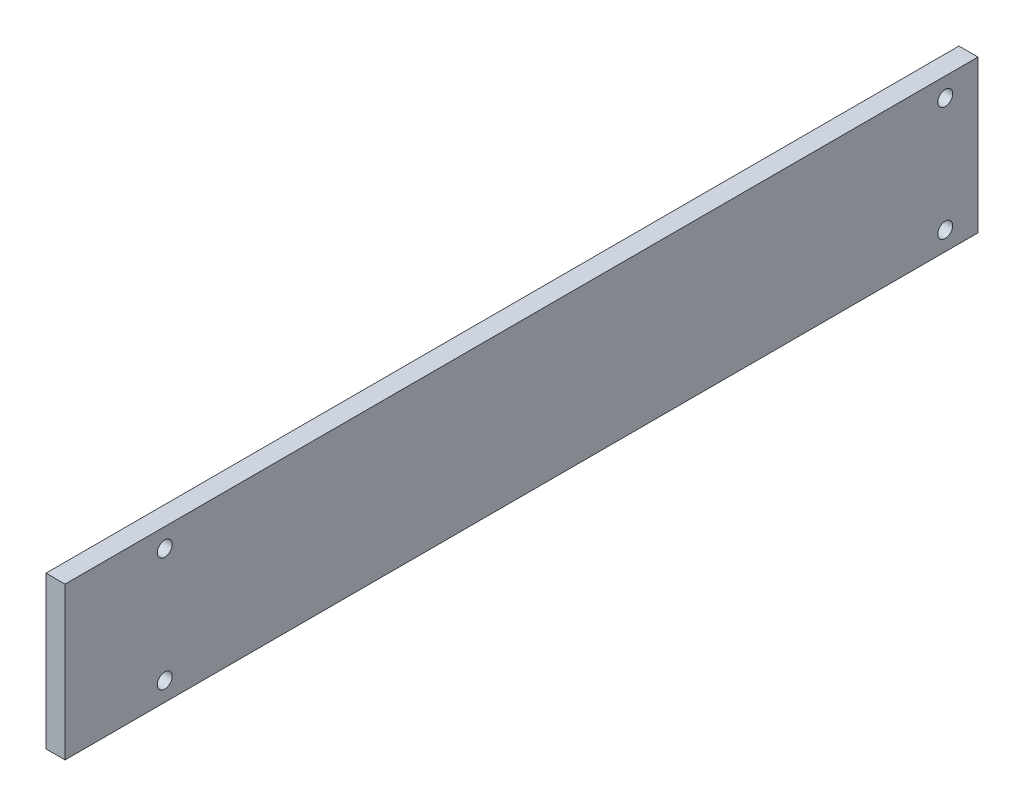
SolidWorks part; units mm, degrees
material "6061-T6 (SS)"
ref_plane "Front Plane" through (0, 0, 0) normal (0, 0, 1) x (1, 0, 0)
ref_plane "Top Plane" through (0, 0, 0) normal (0, 1, 0) x (1, 0, 0)
ref_plane "Right Plane" through (0, 0, 0) normal (1, 0, 0) x (0, 0, -1)
sketch "Sketch1" plane through (0, 0, 0) normal (1, 0, 0) x (0, 0, -1)
  line L1 (-152.273, 25.4) -> (152.273, 25.4)
  line L2 (-152.273, 25.4) -> (-152.273, -25.4)
  line L3 (-152.273, -25.4) -> (152.273, -25.4)
  line L4 (152.273, 25.4) -> (152.273, -25.4)
  line L5 (-152.273, 25.4) -> (152.273, -25.4) construction
  line L6 (-152.273, -25.4) -> (152.273, 25.4) construction
  point P0 (0, 0)
  dimension "D1" = 50.8
  dimension "D2" = 304.546
extrude "Boss-Extrude1" add sketch "Sketch1" along normal blind 6.35
sketch "Sketch2" plane through (6.35, 0, 0) normal (1, 0, 0) x (0, 0, -1)
  line L0 (152.273, -25.4) -> (152.273, 25.4) construction
  line L1 (-118.999, 19.05) -> (141.351, 19.05) construction
  line L2 (-118.999, 19.05) -> (-118.999, -19.05) construction
  line L3 (-118.999, -19.05) -> (141.351, -19.05) construction
  line L4 (141.351, 19.05) -> (141.351, -19.05) construction
  line L5 (-118.999, 19.05) -> (141.351, -19.05) construction
  line L6 (-118.999, -19.05) -> (141.351, 19.05) construction
  line L7 (-152.273, 25.4) -> (-152.273, -25.4) construction
  point P0 (11.176, 0)
  point P7 (0, 0)
  dimension "D1" = 10.922
  dimension "D2" = 33.274
  dimension "D3" = 38.1
hole_wizard "#10 Clearance Hole1" positions "Sketch3" profile "Sketch4" hole size "#10" standard "ANSI Inch" end condition through all
sketch "Sketch3" plane through (6.35, 0, 0) normal (1, 0, 0) x (0, 0, -1)
  point P0 (-118.999, 19.05)
  point P3 (-118.999, -19.05)
  point P6 (141.351, -19.05)
  point P9 (141.351, 19.05)
sketch "Sketch4" plane through (6.35, 19.05, 118.999) normal (0, 1, 0) x (0, 0, -1)
  line L0 (0, 0) -> (0, 6.35)
  line L1 (0, 6.35) -> (2.4892, 6.35)
  line L2 (2.4892, 6.35) -> (2.4892, 0)
  line L5 (2.4892, 0) -> (0, 0)
  line L11 (0, -6.35) -> (0, 107.95) construction
  dimension "Thru Hole Dia." = 4.9784
  dimension "Thru Hole Depth" = 6.35
